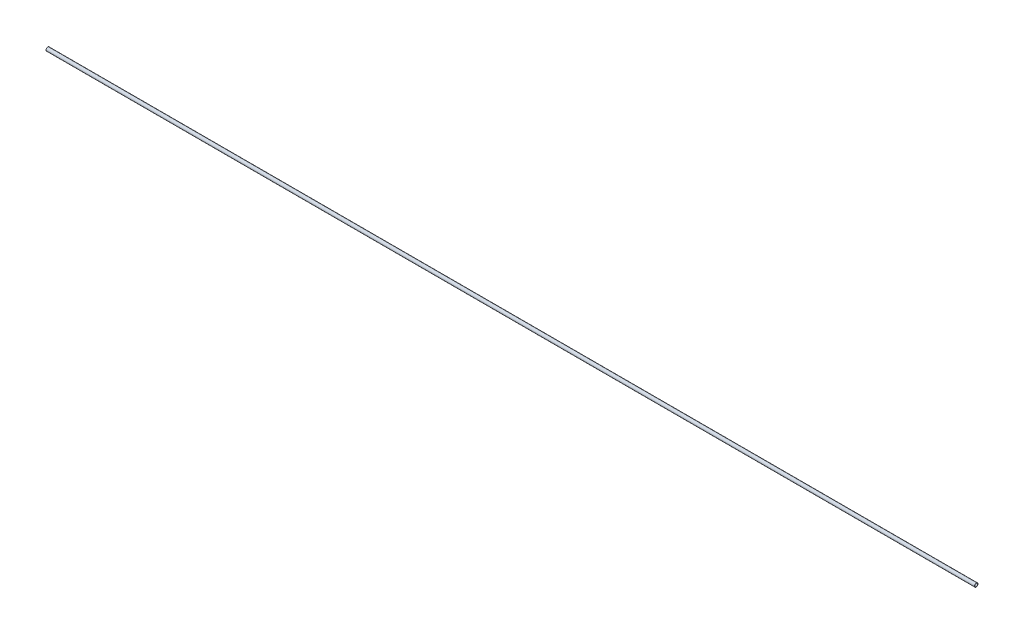
SolidWorks part; units mm, degrees
ref_plane "Alzado" through (0, 0, 0) normal (0, 0, 1) x (1, 0, 0)
ref_plane "Planta" through (0, 0, 0) normal (0, 1, 0) x (1, 0, 0)
ref_plane "Vista lateral" through (0, 0, 0) normal (1, 0, 0) x (0, 0, -1)
sketch "Croquis1" plane through (0, 0, 0) normal (1, 0, 0) x (0, 0, -1)
  circle A0 centre (0, 0) radius 19
  circle A1 centre (0, 0) radius 15
extrude "Saliente-Extruir1" add sketch "Croquis1" along normal blind 10000
